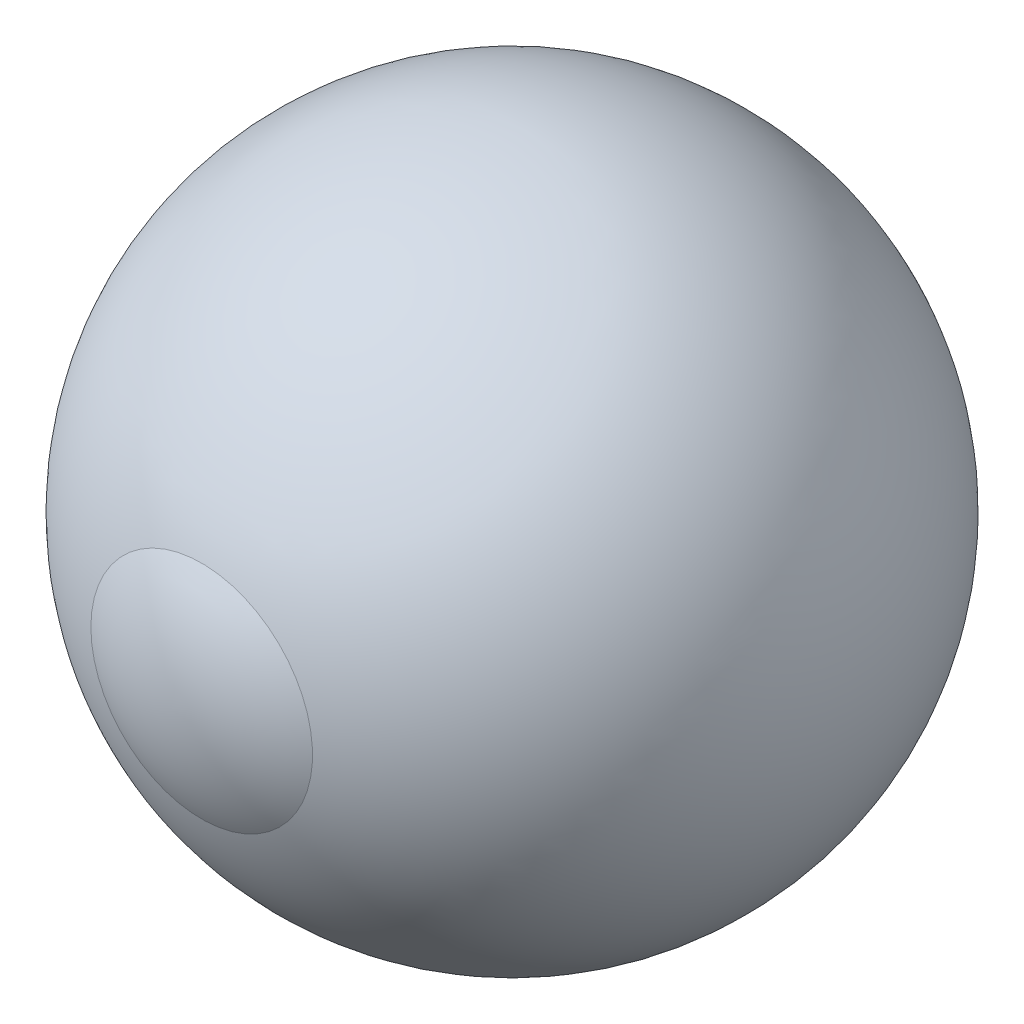
SolidWorks part; units mm, degrees
ref_plane "Front Plane" through (0, 0, 0) normal (0, 0, 1) x (1, 0, 0)
ref_plane "Top Plane" through (0, 0, 0) normal (0, 1, 0) x (1, 0, 0)
ref_plane "Right Plane" through (0, 0, 0) normal (1, 0, 0) x (0, 0, -1)
sketch "eye_anatomy" plane through (0, 0, 0) normal (0, 1, 0) x (1, 0, 0)
  line L0 (0, 33.3682) -> (0, -46.1831) construction
  line L1 (-4, -11.2002) -> (4, -11.2002) construction
  line L2 (-2.6252, -11.2002) -> (2.6252, -11.2002) construction
  arc A0 (4, -11.2002) -> (-4, -11.2002) centre (0, 0) ccw
  arc A1 (-4, -11.2002) -> (4, -11.2002) centre (0, -4.5039) ccw
  arc A2 (-5.0034, -7.3925) -> (5.0034, -7.3925) centre (0, 1.4961) ccw
  arc A3 (-5.0034, -7.3925) -> (5.0034, -7.3925) centre (0, -10.7039) cw
  arc A4 (-2.6252, -11.2002) -> (2.6252, -11.2002) centre (0, -5.2539) ccw
  point P3 (0, 11.8931)
  point P5 (0, -8.7039)
  point P18 (0, -11.7539)
  point P19 (0, -12.3039)
  point P20 (0, -4.7039)
  dimension "D1" = 7.8
  dimension "D2" = 6.5
  dimension "D3" = 10.2
  dimension "D4" = 6
  dimension "D5" = 0.55
  dimension "D9" = 23.7861
  dimension "D6" = 3.05
  dimension "D7" = 4
  dimension "D8" = 24.197
  dimension "D10" = 8
sketch "Sketch2" plane through (0, 0, 0) normal (0, 1, 0) x (1, 0, 0)
  line L0 (0, 11.8931) -> (0, -12.3039) construction
  line L1 (0, 33.3682) -> (0, -46.1831) construction
  line L2 (0, 11.8931) -> (0, -12.3039)
  arc A0 (-4, -11.2002) -> (4, -11.2002) centre (0, -4.5039) ccw construction
  arc A1 (4, -11.2002) -> (-4, -11.2002) centre (0, 0) ccw construction
  arc A5 (0, 11.8931) -> (-4, -11.2002) centre (0, 0) ccw
  arc A9 (-4, -11.2002) -> (0, -12.3039) centre (0, -4.5039) ccw
revolve "eye_revolve" add sketch "Sketch2" angle 360 about L0
